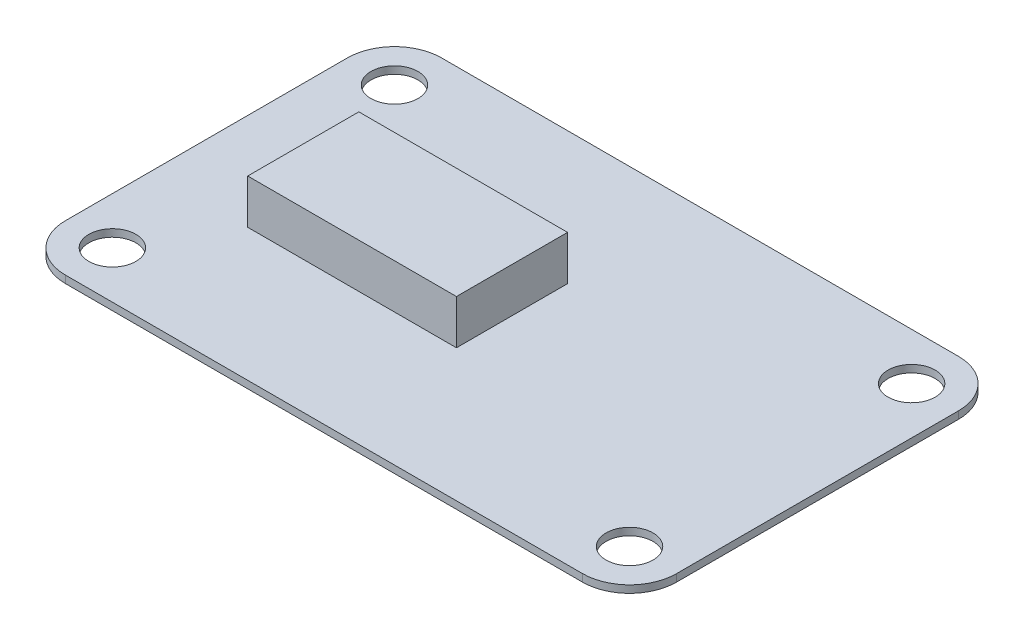
SolidWorks part; units mm, degrees
ref_plane "Front Plane" through (0, 0, 0) normal (0, 0, 1) x (1, 0, 0)
ref_plane "Top Plane" through (0, 0, 0) normal (0, 1, 0) x (1, 0, 0)
ref_plane "Right Plane" through (0, 0, 0) normal (1, 0, 0) x (0, 0, -1)
sketch "Sketch1" plane through (0, 0, 0) normal (0, 1, 0) x (1, 0, 0)
  line L0 (-13.97, 7.62) -> (-13.97, -7.62) construction
  line L1 (13.97, -10.16) -> (-13.97, -10.16)
  line L2 (16.51, -7.62) -> (16.51, 7.62)
  line L3 (13.97, 10.16) -> (-13.97, 10.16)
  line L4 (-16.51, -7.62) -> (-16.51, 7.62)
  line L5 (16.51, -10.16) -> (-16.51, 10.16) construction
  line L6 (16.51, 10.16) -> (-16.51, -10.16) construction
  line L7 (-13.97, -7.62) -> (13.97, -7.62) construction
  line L8 (13.97, -7.62) -> (13.97, 7.62) construction
  line L9 (13.97, 7.62) -> (-13.97, 7.62) construction
  line L10 (0, 7.62) -> (0, -7.62) construction
  line L11 (-16.1999, -8.8363) -> (0, 0) construction
  circle A0 centre (-13.97, 7.62) radius 1.27
  circle A1 centre (13.97, 7.62) radius 1.27
  circle A2 centre (13.97, -7.62) radius 1.27
  circle A3 centre (-13.97, -7.62) radius 1.27
  arc A4 (-13.97, -10.16) -> (-16.51, -7.62) centre (-13.97, -7.62) cw
  arc A5 (13.97, -10.16) -> (16.51, -7.62) centre (13.97, -7.62) ccw
  arc A6 (16.51, 7.62) -> (13.97, 10.16) centre (13.97, 7.62) ccw
  arc A7 (-13.97, 10.16) -> (-16.51, 7.62) centre (-13.97, 7.62) ccw
  point P0 (0, 0)
  dimension "D4" = 2.54
  dimension "D5" = 15.24
  dimension "D1" = 33.02
  dimension "D2" = 20.32
  dimension "D3" = 27.94
extrude "Boss-Extrude1" add sketch "Sketch1" along normal blind 0.4
sketch "Sketch2" plane through (0, 0.4, 0) normal (0, 1, 0) x (1, 0, 0)
  line L1 (-11.2759, 3.0013) -> (0, 3.0013)
  line L2 (-11.2759, 3.0013) -> (-11.2759, -3.0013)
  line L3 (-11.2759, -3.0013) -> (0, -3.0013)
  line L4 (0, 3.0013) -> (0, -3.0013)
  line L5 (-11.2759, 3.0013) -> (0, -3.0013) construction
  line L6 (-11.2759, -3.0013) -> (0, 3.0013) construction
  point P0 (-5.638, 0)
extrude "Boss-Extrude2" add sketch "Sketch2" along normal blind 2.4
